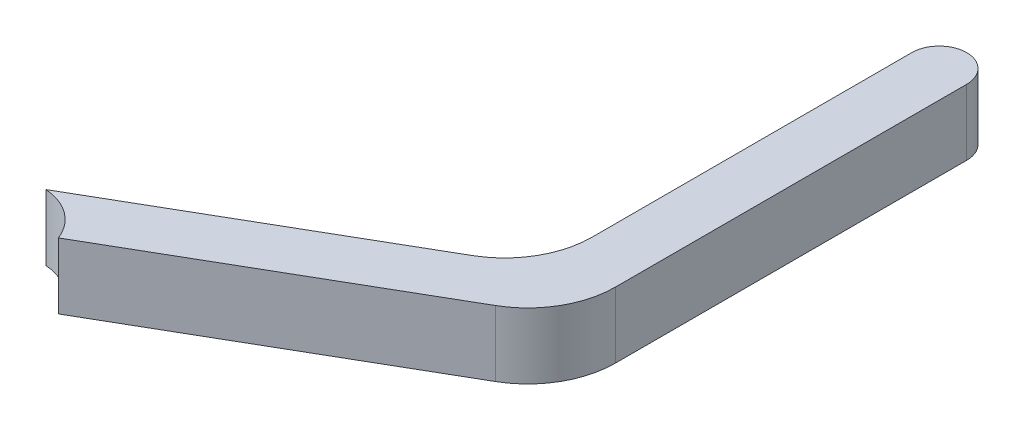
SolidWorks part; units mm, degrees
material "Pine"
ref_plane "Front Plane" through (0, 0, 0) normal (0, 0, 1) x (1, 0, 0)
ref_plane "Top Plane" through (0, 0, 0) normal (0, 1, 0) x (1, 0, 0)
ref_plane "Right Plane" through (0, 0, 0) normal (1, 0, 0) x (0, 0, -1)
sketch "Sketch1" plane through (0, 0, 0) normal (0, 1, 0) x (1, 0, 0)
  line L0 (0, 0) -> (-94.8623, -54.7688) construction
  line L1 (0, 0) -> (0, 111.6203) construction
  line L3 (7.9375, 111.6203) -> (7.9375, -4.5827)
  line L4 (-90.8935, -61.6428) -> (7.9375, -4.5827)
  line L5 (-98.831, -47.8947) -> (-90.8935, -61.6428) construction
  line L6 (-98.831, -47.8947) -> (-7.9375, 4.5827)
  line L7 (-7.9375, 111.6203) -> (-7.9375, 4.5827)
  line L9 (-7.9375, 111.6203) -> (7.9375, 111.6203) construction
  arc A0 (-7.9375, 111.6203) -> (7.9375, 111.6203) centre (0, 111.6203) cw
  arc A2 (-98.831, -47.8947) -> (-90.8935, -61.6428) centre (-94.8623, -54.7688) ccw
  point P14 (-94.8623, -54.7688)
  point P18 (0, 0)
  point P22 (0, 111.6203)
  dimension "D1" = 111.6203
  dimension "D2" = 60
  dimension "D3" = 109.5375
  dimension "D4" = 15.875
extrude "Boss-Extrude1" add sketch "Sketch1" along normal blind 19.05
ref_plane "Plane1" through (0, 0, 0) normal (0.5, 0, 0.866) x (0.866, 0, -0.5)
sketch "Sketch2" plane through (0, 19.05, 0) normal (0, 1, 0) x (1, 0, 0)
  line L0 (-90.8935, -61.6428) -> (7.9375, -4.5827) construction
  line L1 (-84.9318, -58.2009) -> (0, -9.1654) construction
  line L2 (-98.831, -47.8947) -> (-15.875, 0) construction
  line L3 (-84.9318, -58.2009) -> (-90.8935, -61.6428)
  line L4 (-7.9375, 4.5827) -> (-98.831, -47.8947) construction
  line L5 (-90.8935, -61.6428) -> (7.9375, -4.5827) construction
  arc A1 (-98.831, -47.8947) -> (-90.8935, -61.6428) centre (-94.8623, -54.7688) ccw construction
  arc A2 (-98.831, -47.8947) -> (-84.9318, -58.2009) centre (-100.0343, -64.043) cw
  arc A3 (-98.831, -47.8947) -> (-90.8935, -61.6428) centre (-94.8623, -54.7688) ccw
  point P2 (-101.7363, -58.7375)
  line M4 (-90.8935, -61.6428) -> (7.9375, -4.5827)
  arc M11 (-98.831, -47.8947) -> (-90.8935, -61.6428) centre (-94.8623, -54.7688) ccw
  dimension "D1" = 16.1931
  dimension "D2" = 16.8045
extrude "Cut-Extrude1" cut sketch "Sketch2" against normal through all contours A2 M11 M4
fillet "Fillet1" radius 25.4 2 edges at (7.9375, 9.525, 4.5827) (-7.9375, 9.525, -4.5827)
sketch "Sketch3" plane through (0, 19.05, 0) normal (0, 1, 0) x (1, 0, 0)
  line L0 (0, 119.5578) -> (0, 0)
  line L1 (0, 0) -> (-94.8623, -54.7688)
  line L2 (-94.8623, -54.7688) -> (-98.831, -47.8947)
  line L3 (-20.6375, -2.7496) -> (-98.831, -47.8947) construction
  line L4 (-94.8623, -54.7688) -> (-90.8935, -61.6428)
  line L5 (-90.8935, -61.6428) -> (-84.9318, -58.2009)
  line L6 (5.8509, 0) -> (-16.7635, 0)
  line L7 (5.8509, 0) -> (-5.4563, 19.5846)
  arc A0 (7.9375, 111.6203) -> (-7.9375, 111.6203) centre (0, 111.6203) ccw construction
  arc A1 (-4.7625, -11.9151) -> (7.9375, 10.082) centre (-17.4625, 10.082) ccw construction
  arc A2 (-20.6375, -2.7496) -> (-7.9375, 19.2474) centre (-33.3375, 19.2474) ccw construction
ref_plane "Plane2" through (0, 0, -119.5578) normal (0, 0, -1) x (-1, 0, 0)
hole_wizard "1/8 (0.125) Diameter Hole1" positions "Sketch4" profile "Sketch5" hole size "1/8" standard "ANSI Inch"
sketch "Sketch4" plane through (0, 0, 0) normal (0, -1, 0) x (-1, 0, 0)
  line L0 (66.9035, -38.6268) -> (3.403, 1.9647) construction
  line L1 (3.403, 1.9647) -> (0, 94.1578) construction
  line L4 (7.9375, 94.1578) -> (-7.9375, 94.1578) construction
  line L5 (7.9375, 111.6203) -> (7.9375, 19.2474) construction
  line L6 (-7.9375, 10.082) -> (-7.9375, 111.6203) construction
  line L9 (70.8723, -31.7527) -> (62.9348, -45.5009) construction
  line L10 (20.6375, -2.7496) -> (98.831, -47.8947) construction
  line L11 (84.9318, -58.2009) -> (4.7625, -11.9151) construction
  line L13 (-4.5345, -2.618) -> (11.3405, 6.5474) construction
  arc A0 (-7.9375, 10.082) -> (4.7625, -11.9151) centre (17.4625, 10.082) ccw construction
  arc A1 (7.9375, 19.2474) -> (20.6375, -2.7496) centre (33.3375, 19.2474) ccw construction
  arc A2 (7.9375, 111.6203) -> (-7.9375, 111.6203) centre (0, 111.6203) ccw construction
  point P0 (0, 94.1578)
  point P2 (66.9035, -38.6268)
  point P4 (3.403, 1.9647)
  point P29 (66.9035, -38.6268)
  point P32 (0, 94.1578)
  point P45 (4.9136, 2.9894)
  point P46 (3.403, 1.9647)
  point P50 (0, 119.5578)
  point P51 (0, 0)
  point P52 (62.358, -36.0024)
  dimension "D1" = 25.4
  dimension "D2" = 25.4
sketch "Sketch5" plane through (0, 0, -94.1578) normal (1, 0, 0) x (0, 0, -1)
  line L0 (0, 0) -> (0, 12.0791)
  line L1 (0, 12.0791) -> (1.5875, 11.1252)
  line L2 (1.5875, 11.1252) -> (1.5875, 0)
  line L5 (1.5875, 0) -> (0, 0)
  line L10 (0, 12.0791) -> (-1.5875, 11.1252) construction
  line L11 (0, -6.35) -> (0, 107.95) construction
  dimension "Hole Dia." = 3.175
  dimension "Hole Depth" = 11.1252
  dimension "Drill Angle" = 118
